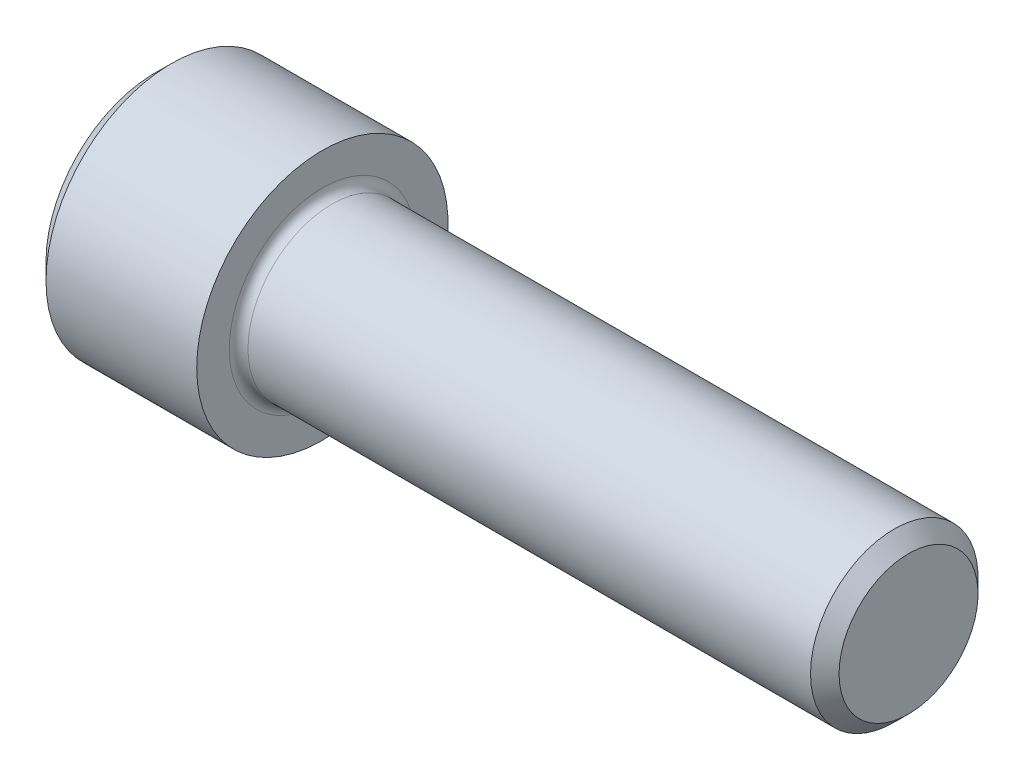
SolidWorks part; units mm, degrees
revolve "Base-Revolve" add sketch "BodySke"
sketch "BodySke" plane through (0, 0, 0) normal (0, 0, 1) x (1, 0, 0)
  line L0 (0, 0) -> (0, 4.1275)
  line L1 (0.635, 4.7625) -> (6.35, 4.7625)
  line L2 (6.35, 4.7625) -> (6.35, 3.175)
  line L3 (6.35, 3.175) -> (28.034, 3.175)
  line L4 (28.575, 2.634) -> (28.575, 0)
  line L5 (28.575, 0) -> (0, 0)
  line L6 (-31.75, 0) -> (127, 0) construction
  line L7 (0, 4.1275) -> (0.635, 4.7625)
  line L8 (28.575, 2.634) -> (28.034, 3.175)
  line L9 (0, -4.1275) -> (0.635, -4.7625) construction
  line L10 (28.575, -2.634) -> (28.034, -3.175) construction
  line L11 (7.2568, 9.525) -> (7.2568, 3.175) construction
  line L12 (6.35, 9.525) -> (6.35, 3.175) construction
  line L13 (-9.525, 9.525) -> (-9.525, 3.175) construction
  dimension "Diameter" = 6.35
  dimension "Head_ht" = 6.35
  dimension "Length" = 22.225
  dimension "Body_ch_ang" = 45
  dimension "Head_dia" = 9.525
  dimension "Head_ch_ang" = 45
  dimension "Head_side_ht" = 5.715
  dimension "Minor_dia" = 5.268
  dimension "Advance" = 0.9068
  dimension "Thread_nom" = 22.225
  dimension "Thread_length" = 38.1
cosmetic thread "ThreadCosmetic" [suppressed]
fillet "Fillet1" radius 0.3556 1 edges at (6.35, 0, 3.175)
ref_plane "Plane1" through (0, 0, 0) normal (0, 0, 1) x (1, 0, 0)
ref_plane "Plane2" through (0, 0, 0) normal (0, 1, 0) x (1, 0, 0)
ref_plane "Plane3" through (0, 0, 0) normal (1, 0, 0) x (0, 0, -1)
sketch "Sketch2" plane through (0, 0, 0) normal (0, 0, 1) x (1, 0, 0)
  line L0 (0, 2.3813) -> (3.048, 2.3813)
  line L1 (3.048, 2.3813) -> (4.4228, 0)
  line L2 (-31.75, 0) -> (127, 0) construction
  line L3 (4.4228, 0) -> (0, 0)
  line L4 (0, 0) -> (0, 2.3813)
  line L5 (0, 4.1275) -> (0, -4.1275) construction
  line L6 (0, 0) -> (47.625, 0) construction
  line L7 (6.35, -4.7625) -> (6.35, 4.7625) construction
  dimension "D1" = 2.3813
  dimension "D2" = 60
revolve "Hex-PreBroach" cut sketch "Sketch2" angle 360 about L6
sketch "Sketch3" plane through (0, 0, 0) normal (-1, 0, 0) x (0, 0.5, 0.866)
  line L0 (1.3748, 2.3813) -> (-1.3748, 2.3813)
  line L1 (-1.3748, 2.3813) -> (-2.7496, 0)
  line L2 (1.3748, 2.3813) -> (2.7496, 0)
  line L3 (1.3748, -2.3812) -> (2.7496, 0)
  line L4 (1.3748, -2.3812) -> (-1.3748, -2.3812)
  line L5 (-1.3748, -2.3812) -> (-2.7496, 0)
  dimension "D1" = 2.3813
  dimension "D2" = 2.3813
  dimension "Hex_size" = 4.7625
extrude "Hex" cut sketch "Sketch3" against normal blind 3.048
sketch "Sketch4" plane through (0, 0, 0) normal (-1, 0, 0) x (0, 0, 1)
  line L0 (0, 0) -> (2.8067, 0)
  line L1 (0, 0) -> (6.1484, 3.5498) construction
  line L2 (0, 0) -> (1.4033, 2.4307)
  line L3 (2.3336, 0.614) -> (2.6851, 0.817)
  line L4 (1.6986, 1.7139) -> (2.0501, 1.9169)
  arc A0 (2.3336, 0.614) -> (1.6986, 1.7139) centre (0, 0) ccw
  arc A1 (2.8067, 0) -> (2.6851, 0.817) centre (0, 0) ccw
  arc A2 (1.4033, 2.4307) -> (2.0501, 1.9169) centre (0, 0) cw
  dimension "D1" = 30
  dimension "D2" = 60
  dimension "Spline_p_dim" = 1.27
  dimension "D3" = 0.635
extrude "Spline" [suppressed] cut sketch "Sketch4" against normal blind 3.048
pattern_circular "CirPattern1" [suppressed] count 6 every 60
sketch "Sketch5" plane through (0, 0, 0) normal (0, 0, 1) x (1, 0, 0)
  line L0 (-31.75, 0) -> (127, 0) construction
  line L2 (0, 4.1275) -> (0, -4.1275) construction
  circle A0 centre (2.159, 0) radius 0.5905
  dimension "Drilled_hole_dia" = 1.1811
  dimension "Drilled_hole_loc" = 2.159
extrude "Hole" [suppressed] cut sketch "Sketch5" against normal through all and the other way through all
pattern_circular "Drilled-4" [suppressed] count 2 every 60
pattern_circular "Drilled-6" [suppressed] count 3 every 60
sketch "ThdSchSke" plane through (0, 0, 0) normal (0, 0, 1) x (1, 0, 0)
  line L0 (7.2568, -2.634) -> (6.878, -3.175)
  line L1 (7.2568, -2.634) -> (7.6356, -3.175)
  line L2 (7.6356, -3.175) -> (7.6356, -3.9688)
  line L3 (-3.175, 0) -> (5.1513, 0) construction
  line L5 (7.6356, -3.9688) -> (6.878, -3.9688)
  line L6 (6.878, -3.9688) -> (6.878, -3.175)
  line L7 (0, 4.1275) -> (0, -4.1275) construction
  dimension "Thread_minor" = 5.268
  dimension "Diameter" = 6.35
  dimension "Start" = 7.2568
revolve "ThreadSchematic" [suppressed] cut sketch "ThdSchSke" angle 360 about L3
pattern_linear "ThdSchPat" [suppressed]
equation "\"D2@Sketch3\" = \"Hex_size@Sketch3\" / 2"
equation "\"D1@Sketch3\" = \"Hex_size@Sketch3\" / 2"
equation "\"D1@Sketch2\" = \"Hex_size@Sketch3\" / 2"
equation "\"D3@Sketch4\" = \"Spline_p_dim@Sketch4\" / 2"
equation "\"Thread_minor@ThreadCosmetic\"  =  \"Minor_dia@BodySke\""
equation "\"D2@CirPattern1\" = 360 / \"Num_teeth@CirPattern1\""
equation "\"Wall_thickness@Sketch2\" = \"Head_ht@BodySke\" - \"Key_eng@Hex\""
equation "\"Thread_length@ThreadCosmetic\" = ((sgn( (\"Length@BodySke\" - \"Advance@BodySke\" ) - \"Thread_nom@BodySke\" )-1)*( (\"Length@BodySke\" - \"Advance@BodySke\" ) - \"Thread_nom@BodySke\" ))/-2+ \"Thread_nom@BodySke\""
equation "\"Thread_minor@ThdSchSke\" = \"Minor_dia@BodySke\""
equation "\"Diameter@ThdSchSke\" = \"Diameter@BodySke\""
equation "\"Overcut@ThdSchSke\" = \"Diameter@BodySke\" * 1.25"
equation "\"Start@ThdSchSke\" = \"Head_ht@BodySke\" + \"Length@BodySke\" - \"Thread_length@ThreadCosmetic\"  '---Non-countersunk---"
equation "\"Num_threads@ThdSchPat\" = int( \"Thread_length@ThreadCosmetic\" / \"Advance@BodySke\" + 0.999 )  + 1"
equation "\"Advance@ThdSchPat\" = \"Thread_length@ThreadCosmetic\" /  (\"Num_threads@ThdSchPat\" - 1) 'relax it"
equation "\"Num_threads@ThdSchPat\" = \"Num_threads@ThdSchPat\" - sgn( \"Num_threads@ThdSchPat\" - 1) '---chamfered tips only---"
